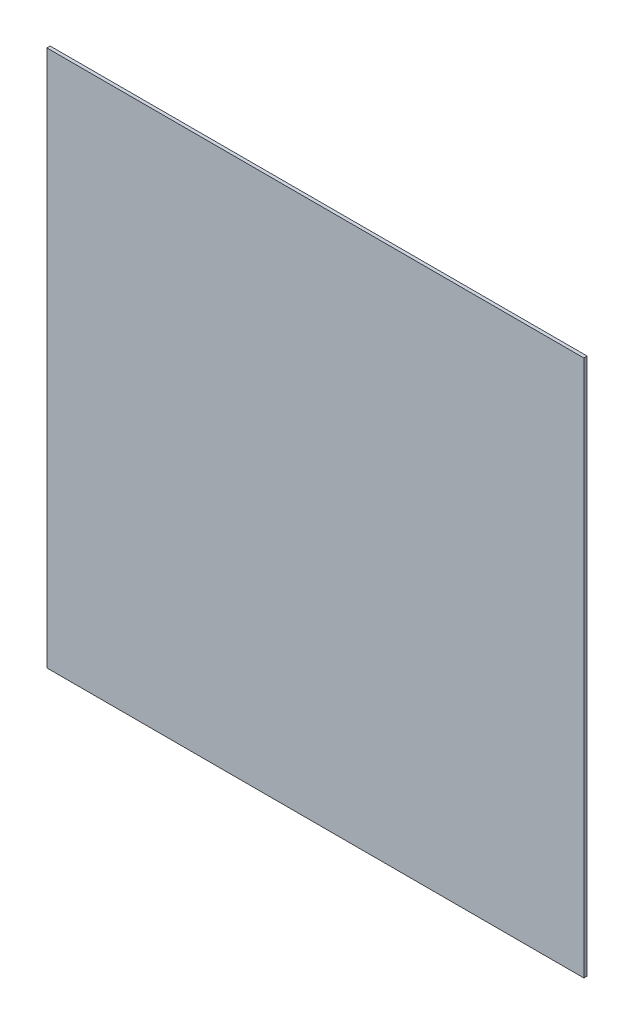
SolidWorks part; units mm, degrees
ref_plane "Front Plane" through (0, 0, 0) normal (0, 0, 1) x (1, 0, 0)
ref_plane "Top Plane" through (0, 0, 0) normal (0, 1, 0) x (1, 0, 0)
ref_plane "Right Plane" through (0, 0, 0) normal (1, 0, 0) x (0, 0, -1)
sketch "Sketch1" plane through (0, 0, 0) normal (0, 0, 1) x (1, 0, 0)
  line L1 (50, 6) -> (62, 6)
  line L2 (50, 6) -> (50, -6)
  line L3 (50, -6) -> (62, -6)
  line L4 (62, 6) -> (62, -6)
extrude "Boss-Extrude1" add sketch "Sketch1" along normal blind 0.0737
